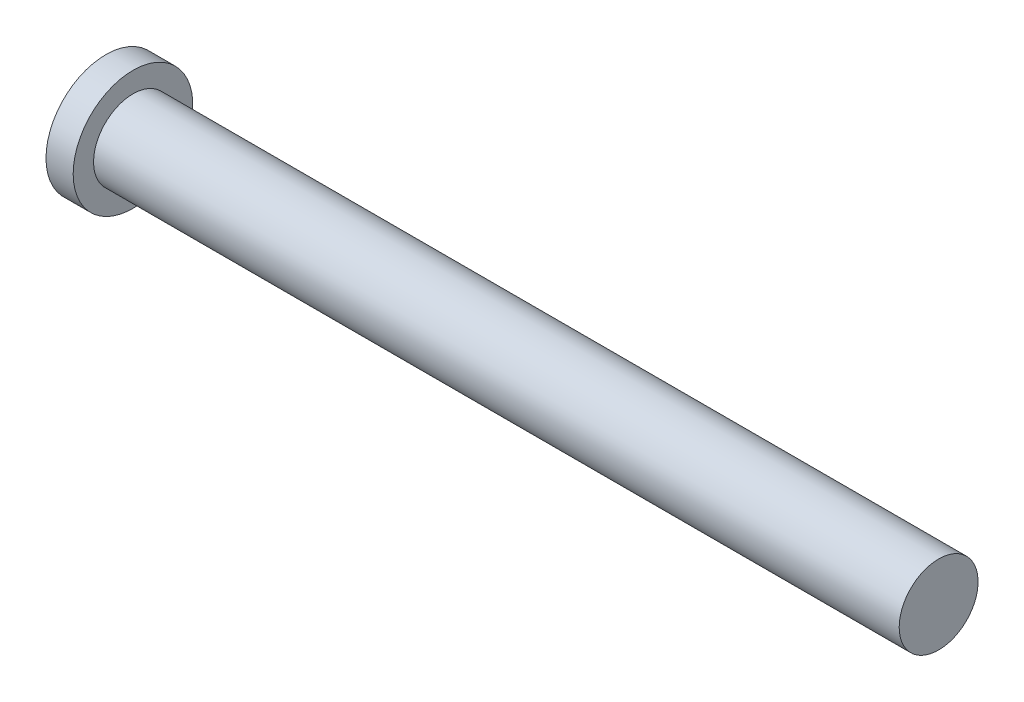
SolidWorks part; units mm, degrees
ref_plane "Ebene vorne" through (0, 0, 0) normal (0, 0, 1) x (1, 0, 0)
ref_plane "Ebene oben" through (0, 0, 0) normal (0, 1, 0) x (1, 0, 0)
ref_plane "Ebene rechts" through (0, 0, 0) normal (1, 0, 0) x (0, 0, -1)
sketch "Skizze1" plane through (0, 0, 0) normal (0, 0, 1) x (1, 0, 0)
  line L0 (0, 0) -> (120.9985, 0) construction
  line L1 (0, 2.25) -> (0, 6.825)
  line L2 (0, 6.825) -> (3.1, 6.825)
  line L3 (3.1, 6.825) -> (3.1, 4.5)
  line L4 (3.1, 4.5) -> (95, 4.5)
  line L5 (95, 4.5) -> (95, 0)
  line L6 (0, 2.25) -> (83.5, 2.25)
  line L7 (83.5, 2.25) -> (83.5, 0)
  line L8 (83.5, 0) -> (95, 0)
  dimension "D1" = 4.5
  dimension "D2" = 2.25
  dimension "D3" = 6.825
  dimension "D4" = 3.1
  dimension "D5" = 95
  dimension "D6" = 83.5
revolve "Rotation1" add sketch "Skizze1" angle 360 about L0
